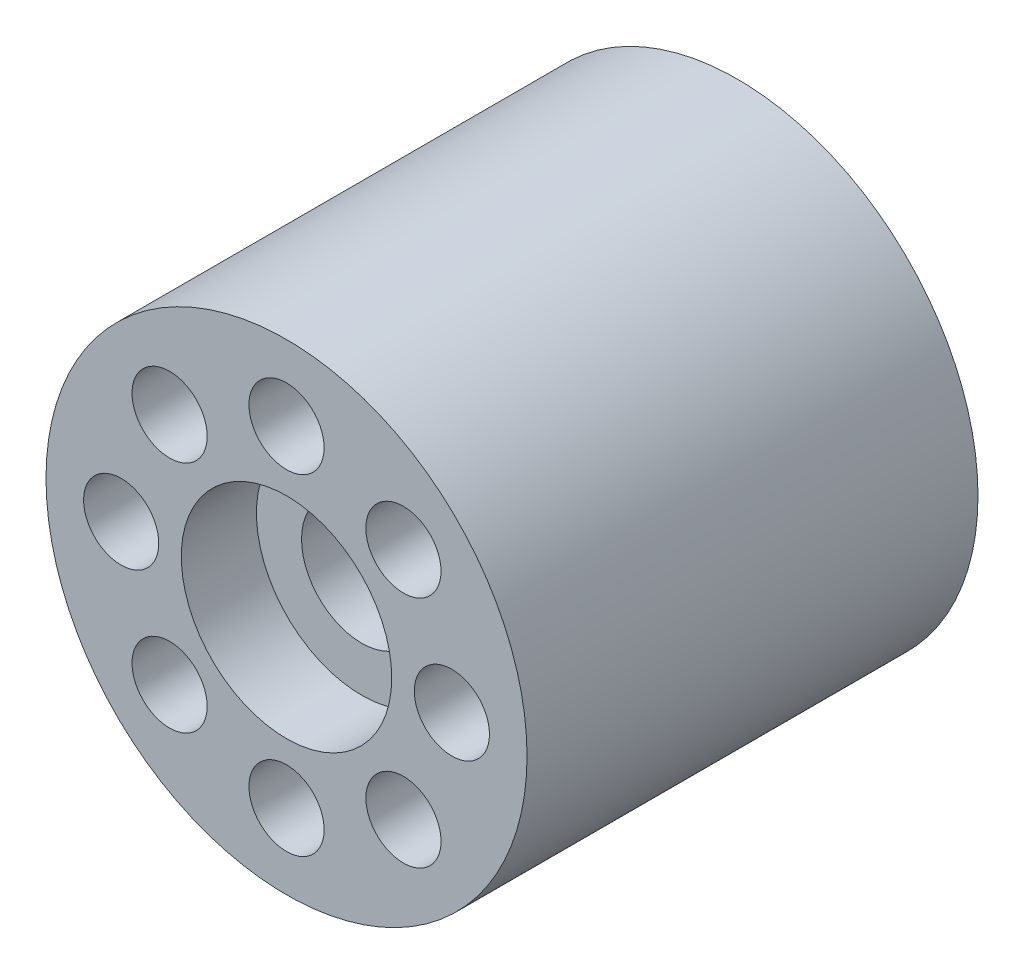
SolidWorks part; units mm, degrees
ref_plane "정면" through (0, 0, 0) normal (0, 0, 1) x (1, 0, 0)
ref_plane "윗면" through (0, 0, 0) normal (0, 1, 0) x (1, 0, 0)
ref_plane "우측면" through (0, 0, 0) normal (1, 0, 0) x (0, 0, -1)
sketch "스케치1" plane through (0, 0, 0) normal (0, 0, 1) x (1, 0, 0)
  circle A0 centre (0, 0) radius 16
  circle A1 centre (0, 0) radius 4
  dimension "32" = 32
  dimension "D2" = 8
extrude "보스-돌출1" add sketch "스케치1" along normal blind 10
sketch "스케치2" plane through (0, 0, 0) normal (0, 0, 1) x (1, 0, 0)
  line L0 (0, 0) -> (0, 11) construction
  circle A0 centre (0, 11) radius 2.5
  dimension "D1" = 5
  dimension "D2" = 11
extrude "컷-돌출1" cut sketch "스케치2" along normal blind 20
pattern_circular "원형 패턴1" count 8 over 360 about axis through (0, 0, 0) along (0, 0, 1) of "컷-돌출1"
sketch "스케치3" plane through (0, 0, 10) normal (0, 0, 1) x (1, 0, 0)
  circle A0 centre (0, 0) radius 7
  dimension "D1" = 14
extrude "컷-돌출2" cut sketch "스케치3" against normal blind 5
sketch "스케치4" plane through (0, 0, 0) normal (0, 0, -1) x (-1, 0, 0)
  circle A0 centre (0, 0) radius 6
  dimension "D1" = 12
extrude "컷-돌출3" cut sketch "스케치4" against normal blind 1
sketch "스케치5" plane through (0, 0, 0) normal (0, 0, -1) x (-1, 0, 0)
  circle A0 centre (0, 0) radius 14
  circle A1 centre (0, 0) radius 16
  circle A2 centre (0, 0) radius 16 construction
  dimension "D1" = 28
extrude "보스-돌출2" add sketch "스케치5" along normal blind 20
sketch "스케치6" plane through (0, 0, 0) normal (1, 0, 0) x (0, 0, -1)
  line L0 (0, 0) -> (40, 0) construction
  line L1 (20, 14) -> (20, 6.1)
  line L2 (20, -16) -> (20, 16) construction
  line L3 (20, 6.1) -> (9.4149, 6.1)
  line L6 (0, 14) -> (20, 14)
  line L7 (0, -14) -> (0, 14) construction
  line L8 (0, 14) -> (0, 13.5)
  line L9 (0, 13.5) -> (9.4149, 6.1)
  dimension "D1" = 40
  dimension "D4" = 12.2
revolve "회전1" add sketch "스케치6" angle 360 about L0
